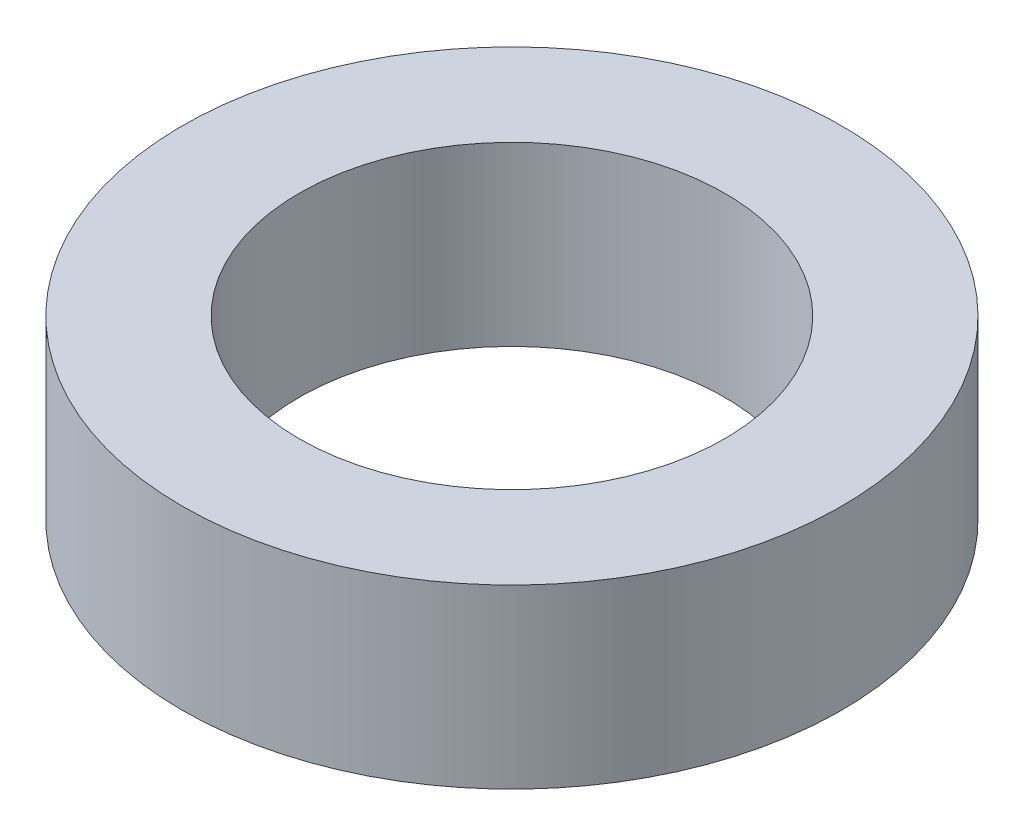
SolidWorks part; units mm, degrees
ref_plane "Front Plane" through (0, 0, 0) normal (0, 0, 1) x (1, 0, 0)
ref_plane "Top Plane" through (0, 0, 0) normal (0, 1, 0) x (1, 0, 0)
ref_plane "Right Plane" through (0, 0, 0) normal (1, 0, 0) x (0, 0, -1)
sketch "Sketch1" plane through (0, 0, 0) normal (0, 1, 0) x (1, 0, 0)
  circle A0 centre (0, 0) radius 5.5
  circle A1 centre (0, 0) radius 3.55
  dimension "D1" = 7.1
  dimension "D2" = 11
extrude "Boss-Extrude1" add sketch "Sketch1" along normal blind 2.95
